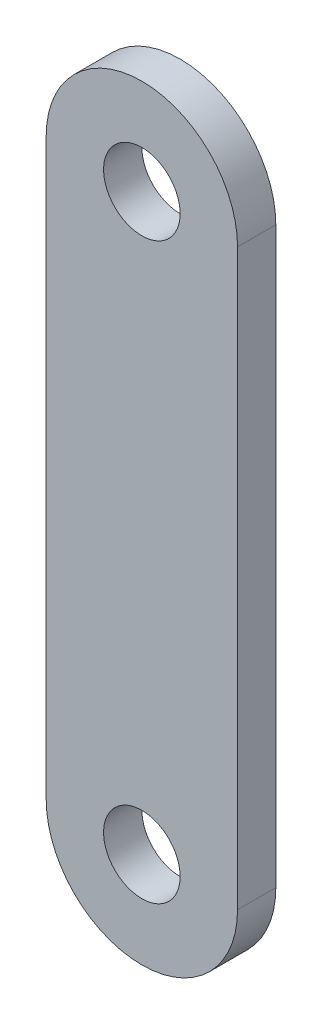
SolidWorks part; units mm, degrees
ref_plane "Alzado" through (0, 0, 0) normal (0, 0, 1) x (1, 0, 0)
ref_plane "Planta" through (0, 0, 0) normal (0, 1, 0) x (1, 0, 0)
ref_plane "Vista lateral" through (0, 0, 0) normal (1, 0, 0) x (0, 0, -1)
sketch "Croquis1" plane through (0, 0, 0) normal (0, 0, 1) x (1, 0, 0)
  line L0 (0, 0) -> (50, 0) construction
  line L1 (50, 0) -> (50, 150)
  line L2 (50, 150) -> (0, 150) construction
  line L3 (0, 150) -> (0, 0)
  arc A0 (0, 0) -> (50, 0) centre (25, 0) ccw
  arc A1 (50, 150) -> (0, 150) centre (25, 150) ccw
  circle A2 centre (25, 150) radius 10
  circle A3 centre (25, 0) radius 10
  dimension "D2" = 20
  dimension "D3" = 20
  dimension "D1" = 50
  dimension "D4" = 150
extrude "Saliente-Extruir1" add sketch "Croquis1" along normal blind 10
